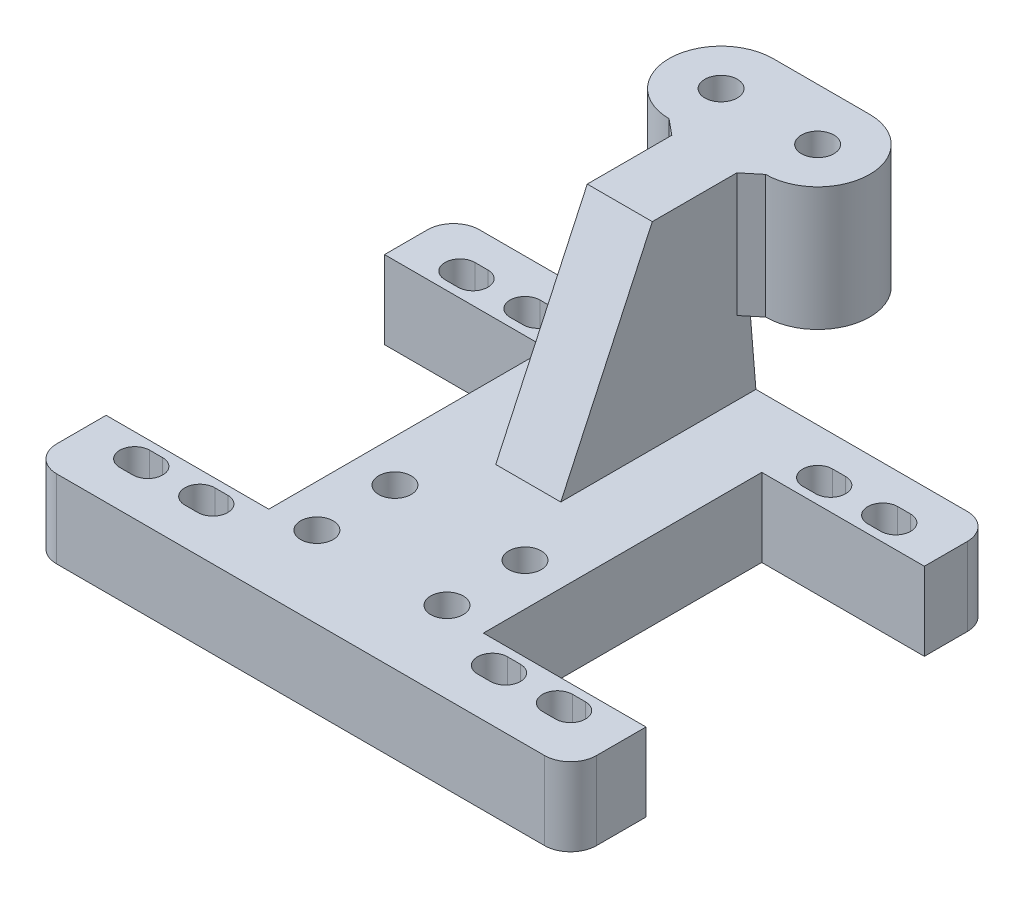
SolidWorks part; units mm, degrees
ref_plane "Plan de face" through (0, 0, 0) normal (0, 0, 1) x (1, 0, 0)
ref_plane "Plan de dessus" through (0, 0, 0) normal (0, 1, 0) x (1, 0, 0)
ref_plane "Plan de droite" through (0, 0, 0) normal (1, 0, 0) x (0, 0, -1)
sketch "Esquisse1" plane through (0, 8.7, 0) normal (0, -1, 0) x (1, 0, 0)
  line L0 (22.5, 55.4) -> (32.5, 55.4) construction
  line L1 (22.5, 105.4) -> (32.5, 105.4) construction
  line L2 (27.5, 105.4) -> (27.5, 55.4) construction
  line L3 (21.5, 55.4) -> (23.5, 55.4) construction
  line L4 (21.5, 57.7) -> (23.5, 57.7)
  line L5 (21.5, 53.1) -> (23.5, 53.1)
  line L6 (31.5, 55.4) -> (33.5, 55.4) construction
  line L7 (31.5, 57.7) -> (33.5, 57.7)
  line L8 (27.5, 80.4) -> (15.3445, 80.4) construction
  line L9 (31.5, 53.1) -> (33.5, 53.1)
  line L10 (21.5, 105.4) -> (23.5, 105.4) construction
  line L11 (21.5, 107.7) -> (23.5, 107.7)
  line L12 (21.5, 103.1) -> (23.5, 103.1)
  line L13 (31.5, 105.4) -> (33.5, 105.4) construction
  line L14 (31.5, 107.7) -> (33.5, 107.7)
  line L15 (31.5, 103.1) -> (33.5, 103.1)
  line L16 (0, 0) -> (0, 113.4) construction
  line L17 (38.5, 59) -> (41.5, 59)
  line L18 (41.5, 48.4) -> (0, 48.4)
  line L19 (0, 48.4) -> (0, 113.4)
  line L20 (0, 113.4) -> (41.5, 113.4)
  line L21 (41.5, 59) -> (41.5, 48.4)
  line L22 (41.5, 113.4) -> (41.5, 101.8)
  line L23 (41.5, 101.8) -> (38.5, 101.8)
  line L25 (0, 110.0019) -> (0, 114.4435) construction
  line L27 (38.5, 59) -> (38.5, 101.8)
  line L28 (16.5, 59) -> (38.5, 59)
  line L29 (16.5, 101.8) -> (16.5, 59)
  line L30 (38.5, 101.8) -> (16.5, 101.8)
  line L31 (38.5, 59) -> (38.5, 101.8) construction
  line L32 (16.5, 59) -> (38.5, 59)
  line L33 (16.5, 101.8) -> (16.5, 59)
  line L34 (38.5, 101.8) -> (16.5, 101.8)
  arc A0 (31.5, 57.7) -> (31.5, 53.1) centre (31.5, 55.4) ccw
  arc A1 (21.5, 57.7) -> (21.5, 53.1) centre (21.5, 55.4) ccw
  arc A2 (33.5, 53.1) -> (33.5, 57.7) centre (33.5, 55.4) ccw
  arc A3 (23.5, 53.1) -> (23.5, 57.7) centre (23.5, 55.4) ccw
  arc A4 (21.5, 107.7) -> (21.5, 103.1) centre (21.5, 105.4) ccw
  arc A5 (23.5, 103.1) -> (23.5, 107.7) centre (23.5, 105.4) ccw
  arc A6 (31.5, 107.7) -> (31.5, 103.1) centre (31.5, 105.4) ccw
  arc A7 (33.5, 103.1) -> (33.5, 107.7) centre (33.5, 105.4) ccw
  point P9 (32.5, 55.4)
  point P11 (22.5, 55.4)
  point P28 (22.5, 105.4)
  point P39 (32.5, 105.4)
  dimension "D2" = 2.3
  dimension "D6" = 3
  dimension "D1" = 2
  dimension "D3" = 1
  dimension "D4" = 2
  dimension "D5" = 2
  dimension "D10" = 7
  dimension "D11" = 65
extrude "Boss.-Extru.1" add sketch "Esquisse1" along normal blind 12
mirror "Symétrie1" about plane through (0, 0, 0) normal (1, 0, 0) of "Boss.-Extru.1"
ref_plane "Plan1" through (0, 29.5, 0) normal (0, 1, 0) x (1, 0, 0)
sketch "Esquisse6" plane through (0, 29.5, 0) normal (0, 1, 0) x (1, 0, 0)
  line L0 (0, 0) -> (0, -85.5357) construction
  line L1 (-7.4248, -41.3297) -> (7.4248, -41.3297) construction
  line L2 (-7.4248, -33.3297) -> (7.4248, -33.3297)
  line L3 (-7.4248, -49.3297) -> (7.4248, -49.3297)
  line L4 (0, 0) -> (0, -41.3297) construction
  arc A0 (-7.4248, -33.3297) -> (-7.4248, -49.3297) centre (-7.4248, -41.3297) ccw
  arc A1 (7.4248, -49.3297) -> (7.4248, -33.3297) centre (7.4248, -41.3297) ccw
  circle A2 centre (7.4248, -41.3297) radius 2.5
  circle A3 centre (-7.4248, -41.3297) radius 2.5
  point P4 (0, -41.3297)
  dimension "D1" = 8
  dimension "D2" = 5
extrude "Boss.-Extru.2" add sketch "Esquisse6" along normal mid plane 19 separate body
sketch "Esquisse7" plane through (0, 0, 0) normal (1, 0, 0) x (0, 0, -1)
  line L0 (-49.3297, 20) -> (-49.3297, 39)
  line L1 (-49.3297, 39) -> (-49.3297, 20) construction
  line L2 (-33.3297, 39) -> (-49.3297, 39) construction
  line L3 (-49.3297, 39) -> (-64.3297, 39)
  line L4 (-104.53, 8.7) -> (-48.4, 8.7) construction
  line L5 (-89.53, 8.7) -> (-104.53, 8.7) construction
  line L6 (-64.3297, 39) -> (-78.4, 8.7)
  line L7 (-48.4, 8.7) -> (-49.3297, 20)
  line L10 (-48.4, 8.7) -> (-78.4, 8.7)
  dimension "D1" = 30
  dimension "D2" = 15
extrude "Boss.-Extru.3" add sketch "Esquisse7" along normal mid plane 10
sketch "Esquisse8" plane through (0, 8.7, 0) normal (0, 1, 0) x (1, 0, 0)
  line L0 (0, 0) -> (0, -113.4) construction
  line L1 (41.5, -113.4) -> (-41.5, -113.4) construction
  line L2 (-10, -88.9) -> (-10, -100.9) construction
  circle A0 centre (-10, -88.9) radius 2.5
  circle A1 centre (-10, -100.9) radius 2.5
  circle A2 centre (10, -100.9) radius 2.5
  circle A3 centre (10, -88.9) radius 2.5
  dimension "D1" = 5
  dimension "D4" = 10
  dimension "D2" = 20
  dimension "D3" = 12
fillet "Congé1" radius 4 4 edges at (-41.5, 2.7, 48.4) (41.5, 2.7, 48.4) (41.5, 2.7, 113.4) (-41.5, 2.7, 113.4)
extrude "Enlèv. mat.-Extru.1" cut sketch "Esquisse8" against normal through all
sketch "Esquisse9" plane through (0, 39, 0) normal (0, 1, 0) x (1, 0, 0)
  line L0 (-7.4248, -49.3297) -> (-5, -51.3297)
  line L1 (-7.4248, -49.3297) -> (-5, -49.3297) construction
  line L2 (-5, -49.3297) -> (-5, -64.3297) construction
  line L3 (-5, -51.3297) -> (-5, -49.3297)
  line L4 (-5, -49.3297) -> (-7.4248, -49.3297)
  line L5 (0, 0) -> (0, -113.4) construction
  line L6 (37.5, -113.4) -> (-37.5, -113.4) construction
  line L7 (5, -51.3297) -> (5, -49.3297)
  line L8 (7.4248, -49.3297) -> (5, -51.3297)
  line L9 (5, -49.3297) -> (7.4248, -49.3297)
  dimension "D1" = 2
extrude "Boss.-Extru.4" add sketch "Esquisse9" against normal up to surface (19 mm away) up to face at (0, 20, 43.9963)
